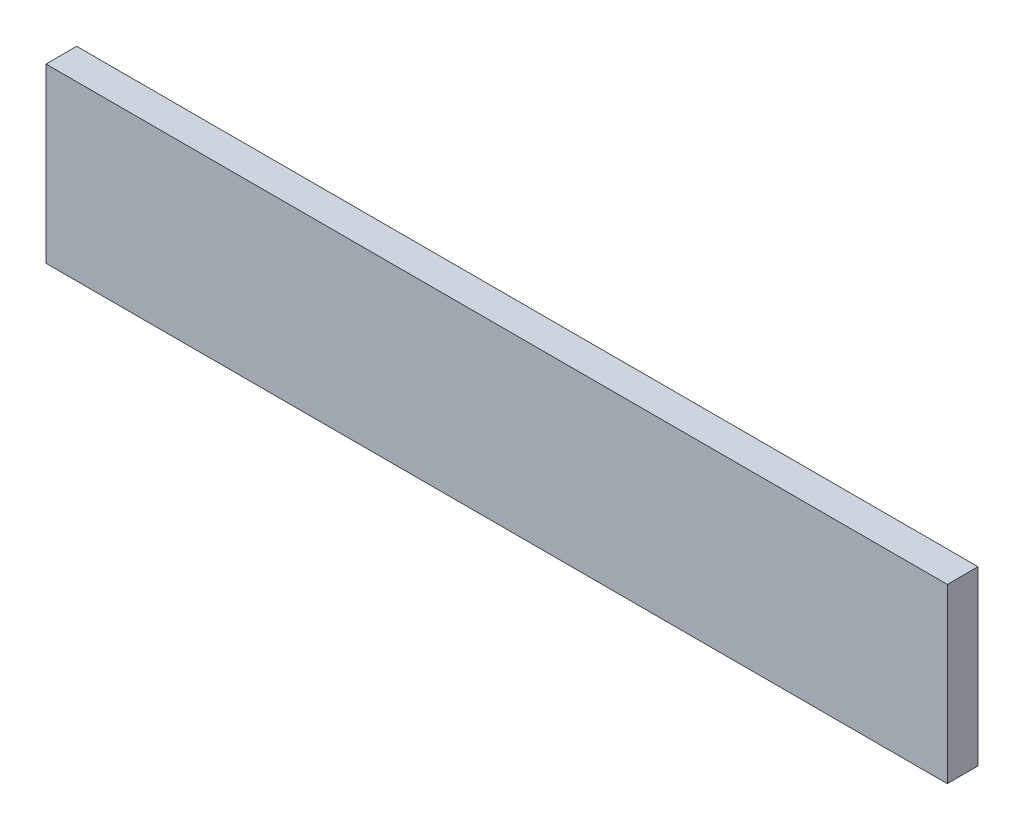
SolidWorks part; units mm, degrees
material "PF"
ref_plane "前视基准面" through (0, 0, 0) normal (0, 0, 1) x (1, 0, 0)
ref_plane "上视基准面" through (0, 0, 0) normal (0, 1, 0) x (1, 0, 0)
ref_plane "右视基准面" through (0, 0, 0) normal (1, 0, 0) x (0, 0, -1)
other "Configuration Table"
sketch "草图1" plane through (0, 0, 0) normal (0, 0, 1) x (1, 0, 0)
  line L1 (-115.1421, 41.2895) -> (119.8579, 41.2895)
  line L2 (-115.1421, 41.2895) -> (-115.1421, -3.7105)
  line L3 (-115.1421, -3.7105) -> (119.8579, -3.7105)
  line L4 (119.8579, 41.2895) -> (119.8579, -3.7105)
  dimension "D1" = 235
  dimension "D2" = 45
extrude "凸台-拉伸1" add sketch "草图1" along normal blind 8
